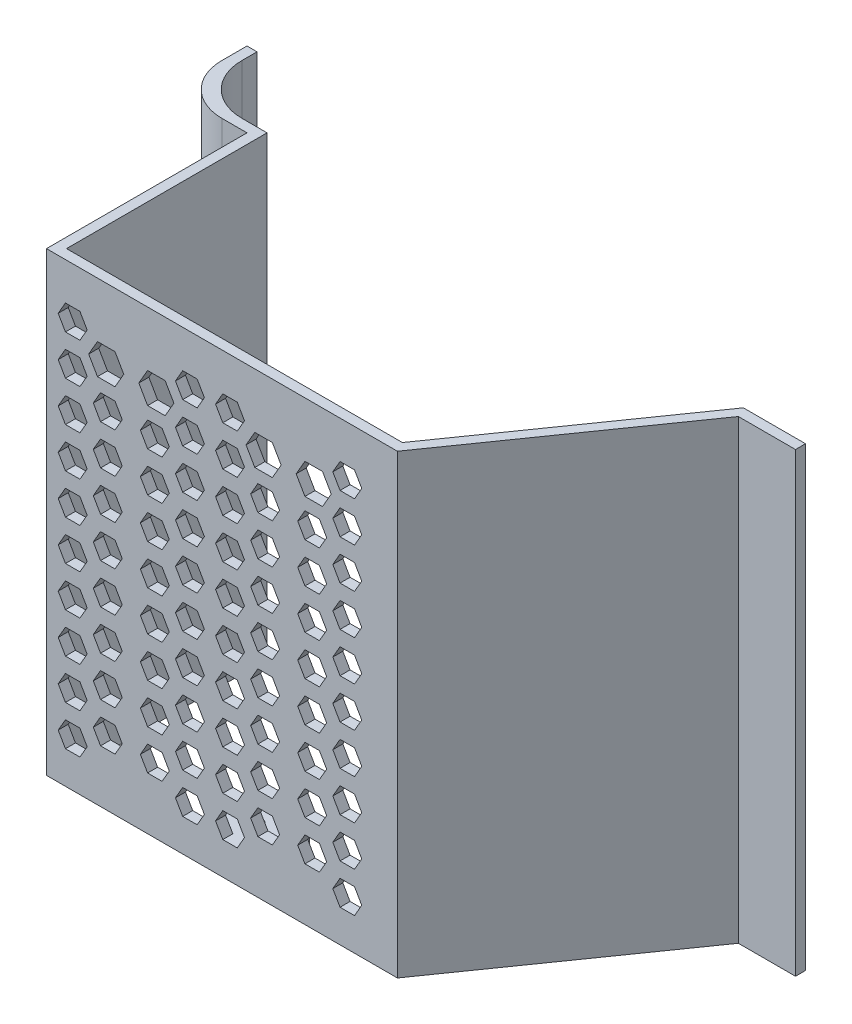
SolidWorks part; units mm, degrees
ref_plane "Ön Düzlem" through (0, 0, 0) normal (0, 0, 1) x (1, 0, 0)
ref_plane "Üst Düzlem" through (0, 0, 0) normal (0, 1, 0) x (1, 0, 0)
ref_plane "Sağ Düzlem" through (0, 0, 0) normal (1, 0, 0) x (0, 0, -1)
sketch "Çizim1" plane through (0, 0, 0) normal (0, 1, 0) x (1, 0, 0)
  line L0 (0, 0) -> (70, 0)
  line L5 (0, 0) -> (0, 30)
  line L8 (0, 30) -> (-3, 30)
  line L9 (-13, 40) -> (-13, 42)
  line L10 (-13, 42) -> (-11, 42)
  line L11 (70, 0) -> (99.4087, 42)
  line L12 (-1, 32) -> (2, 32)
  line L13 (2, 32) -> (2, 2)
  line L14 (2, 2) -> (69, 2)
  line L15 (69, 2) -> (97.0083, 42)
  line L16 (97.0083, 42) -> (99.4087, 42)
  arc A0 (-3, 30) -> (-13, 40) centre (-3, 40) cw
  arc A1 (-11, 42) -> (-1, 32) centre (-1, 42) ccw
  dimension "D3" = 10
  dimension "D1" = 70
  dimension "D2" = 30
extrude "Yükseklik-Ekstrüzyon1" add sketch "Çizim1" along normal blind 91
sketch "Çizim2" plane through (0, 0, 0) normal (0, 0, 1) x (1, 0, 0)
  line L0 (70, 91) -> (60, 91)
  line L1 (0, 91) -> (70, 91) construction
  line L2 (61.4434, 75.5) -> (62.8868, 73)
  line L3 (58.5566, 75.5) -> (61.4434, 75.5)
  line L4 (62.8868, 65) -> (61.4434, 67.5)
  line L5 (57.1132, 73) -> (58.5566, 75.5)
  line L6 (58.5566, 70.5) -> (57.1132, 73)
  line L7 (62.8868, 81) -> (61.4434, 83.5)
  line L8 (61.4434, 83.5) -> (58.5566, 83.5)
  line L9 (58.5566, 83.5) -> (57.1132, 81)
  line L10 (57.1132, 81) -> (58.5566, 78.5)
  line L11 (58.5566, 78.5) -> (61.4434, 78.5)
  line L12 (61.4434, 78.5) -> (62.8868, 81)
  line L13 (61.4434, 70.5) -> (58.5566, 70.5)
  line L14 (62.8868, 73) -> (61.4434, 70.5)
  line L15 (61.4434, 43.5) -> (62.8868, 41)
  line L16 (61.4434, 67.5) -> (58.5566, 67.5)
  line L17 (61.4434, 59.5) -> (62.8868, 57)
  line L18 (58.5566, 59.5) -> (61.4434, 59.5)
  line L19 (57.1132, 57) -> (58.5566, 59.5)
  line L20 (58.5566, 54.5) -> (57.1132, 57)
  line L21 (61.4434, 54.5) -> (58.5566, 54.5)
  line L22 (62.8868, 57) -> (61.4434, 54.5)
  line L23 (58.5566, 67.5) -> (57.1132, 65)
  line L24 (57.1132, 65) -> (58.5566, 62.5)
  line L25 (58.5566, 62.5) -> (61.4434, 62.5)
  line L26 (61.4434, 62.5) -> (62.8868, 65)
  line L27 (61.4434, 11.5) -> (62.8868, 9)
  line L28 (58.5566, 43.5) -> (61.4434, 43.5)
  line L29 (57.1132, 41) -> (58.5566, 43.5)
  line L30 (58.5566, 38.5) -> (57.1132, 41)
  line L31 (62.8868, 49) -> (61.4434, 51.5)
  line L32 (61.4434, 51.5) -> (58.5566, 51.5)
  line L33 (58.5566, 51.5) -> (57.1132, 49)
  line L34 (57.1132, 49) -> (58.5566, 46.5)
  line L35 (58.5566, 46.5) -> (61.4434, 46.5)
  line L36 (61.4434, 46.5) -> (62.8868, 49)
  line L37 (61.4434, 38.5) -> (58.5566, 38.5)
  line L38 (62.8868, 33) -> (61.4434, 35.5)
  line L39 (61.4434, 35.5) -> (58.5566, 35.5)
  line L40 (61.4434, 27.5) -> (62.8868, 25)
  line L41 (58.5566, 27.5) -> (61.4434, 27.5)
  line L42 (57.1132, 25) -> (58.5566, 27.5)
  line L43 (58.5566, 22.5) -> (57.1132, 25)
  line L44 (61.4434, 22.5) -> (58.5566, 22.5)
  line L45 (62.8868, 25) -> (61.4434, 22.5)
  line L46 (58.5566, 35.5) -> (57.1132, 33)
  line L47 (57.1132, 33) -> (58.5566, 30.5)
  line L48 (62.8868, 41) -> (61.4434, 38.5)
  line L49 (58.5566, 30.5) -> (61.4434, 30.5)
  line L50 (61.4434, 30.5) -> (62.8868, 33)
  line L51 (42.1699, 10.5) -> (40.7265, 13)
  line L52 (58.5566, 11.5) -> (61.4434, 11.5)
  line L53 (57.1132, 9) -> (58.5566, 11.5)
  line L54 (58.5566, 6.5) -> (57.1132, 9)
  line L55 (62.8868, 17) -> (61.4434, 19.5)
  line L56 (61.4434, 19.5) -> (58.5566, 19.5)
  line L57 (58.5566, 19.5) -> (57.1132, 17)
  line L58 (57.1132, 17) -> (58.5566, 14.5)
  line L59 (58.5566, 14.5) -> (61.4434, 14.5)
  line L60 (61.4434, 14.5) -> (62.8868, 17)
  line L61 (61.4434, 6.5) -> (58.5566, 6.5)
  line L62 (62.8868, 9) -> (61.4434, 6.5)
  line L63 (54.4434, 71.5) -> (55.8868, 69)
  line L64 (51.5566, 71.5) -> (54.4434, 71.5)
  line L65 (56.8066, 77) -> (55.0566, 80.0311)
  line L66 (55.0566, 80.0311) -> (51.5566, 80.0311)
  line L67 (51.5566, 80.0311) -> (49.8066, 77)
  line L68 (49.8066, 77) -> (51.5566, 73.9689)
  line L69 (51.5566, 73.9689) -> (55.0566, 73.9689)
  line L70 (55.0566, 73.9689) -> (56.8066, 77)
  line L71 (50.1132, 69) -> (51.5566, 71.5)
  line L72 (51.5566, 66.5) -> (50.1132, 69)
  line L73 (54.4434, 66.5) -> (51.5566, 66.5)
  line L74 (55.8868, 69) -> (54.4434, 66.5)
  line L75 (55.8868, 61) -> (54.4434, 63.5)
  line L76 (54.4434, 63.5) -> (51.5566, 63.5)
  line L77 (51.5566, 63.5) -> (50.1132, 61)
  line L78 (50.1132, 61) -> (51.5566, 58.5)
  line L79 (54.4434, 55.5) -> (55.8868, 53)
  line L80 (51.5566, 55.5) -> (54.4434, 55.5)
  line L81 (50.1132, 53) -> (51.5566, 55.5)
  line L82 (51.5566, 50.5) -> (50.1132, 53)
  line L83 (54.4434, 50.5) -> (51.5566, 50.5)
  line L84 (55.8868, 53) -> (54.4434, 50.5)
  line L85 (51.5566, 58.5) -> (54.4434, 58.5)
  line L86 (54.4434, 58.5) -> (55.8868, 61)
  line L87 (54.4434, 39.5) -> (55.8868, 37)
  line L88 (51.5566, 39.5) -> (54.4434, 39.5)
  line L89 (55.8868, 45) -> (54.4434, 47.5)
  line L90 (54.4434, 47.5) -> (51.5566, 47.5)
  line L91 (51.5566, 47.5) -> (50.1132, 45)
  line L92 (50.1132, 45) -> (51.5566, 42.5)
  line L93 (51.5566, 42.5) -> (54.4434, 42.5)
  line L94 (54.4434, 42.5) -> (55.8868, 45)
  line L95 (50.1132, 37) -> (51.5566, 39.5)
  line L96 (51.5566, 34.5) -> (50.1132, 37)
  line L97 (54.4434, 34.5) -> (51.5566, 34.5)
  line L98 (55.8868, 37) -> (54.4434, 34.5)
  line L99 (55.8868, 29) -> (54.4434, 31.5)
  line L100 (54.4434, 31.5) -> (51.5566, 31.5)
  line L101 (51.5566, 31.5) -> (50.1132, 29)
  line L102 (50.1132, 29) -> (51.5566, 26.5)
  line L103 (54.4434, 23.5) -> (55.8868, 21)
  line L104 (51.5566, 23.5) -> (54.4434, 23.5)
  line L105 (50.1132, 21) -> (51.5566, 23.5)
  line L106 (51.5566, 18.5) -> (50.1132, 21)
  line L107 (54.4434, 18.5) -> (51.5566, 18.5)
  line L108 (55.8868, 21) -> (54.4434, 18.5)
  line L109 (51.5566, 26.5) -> (54.4434, 26.5)
  line L110 (54.4434, 26.5) -> (55.8868, 29)
  line L111 (55.8868, 13) -> (54.4434, 15.5)
  line L112 (54.4434, 15.5) -> (51.5566, 15.5)
  line L113 (51.5566, 15.5) -> (50.1132, 13)
  line L114 (50.1132, 13) -> (51.5566, 10.5)
  line L115 (51.5566, 10.5) -> (54.4434, 10.5)
  line L116 (54.4434, 10.5) -> (55.8868, 13)
  line L117 (30.0566, 75.5) -> (31.5, 73)
  line L118 (45.0566, 10.5) -> (42.1699, 10.5)
  line L119 (46.5, 13) -> (45.0566, 10.5)
  line L120 (45.0566, 15.5) -> (46.5, 13)
  line L121 (42.1699, 15.5) -> (45.0566, 15.5)
  line L122 (40.7265, 13) -> (42.1699, 15.5)
  line L123 (42.1699, 26.5) -> (40.7265, 29)
  line L124 (45.0566, 26.5) -> (42.1699, 26.5)
  line L125 (40.7265, 21) -> (42.1699, 18.5)
  line L126 (42.1699, 18.5) -> (45.0566, 18.5)
  line L127 (45.0566, 18.5) -> (46.5, 21)
  line L128 (46.5, 21) -> (45.0566, 23.5)
  line L129 (45.0566, 23.5) -> (42.1699, 23.5)
  line L130 (42.1699, 23.5) -> (40.7265, 21)
  line L131 (46.5, 29) -> (45.0566, 26.5)
  line L132 (45.0566, 31.5) -> (46.5, 29)
  line L133 (42.1699, 31.5) -> (45.0566, 31.5)
  line L134 (40.7265, 29) -> (42.1699, 31.5)
  line L135 (40.7265, 37) -> (42.1699, 34.5)
  line L136 (42.1699, 34.5) -> (45.0566, 34.5)
  line L137 (45.0566, 34.5) -> (46.5, 37)
  line L138 (46.5, 37) -> (45.0566, 39.5)
  line L139 (42.1699, 42.5) -> (40.7265, 45)
  line L140 (45.0566, 42.5) -> (42.1699, 42.5)
  line L141 (46.5, 45) -> (45.0566, 42.5)
  line L142 (45.0566, 47.5) -> (46.5, 45)
  line L143 (42.1699, 47.5) -> (45.0566, 47.5)
  line L144 (40.7265, 45) -> (42.1699, 47.5)
  line L145 (45.0566, 39.5) -> (42.1699, 39.5)
  line L146 (42.1699, 39.5) -> (40.7265, 37)
  line L147 (42.1699, 58.5) -> (40.7265, 61)
  line L148 (45.0566, 58.5) -> (42.1699, 58.5)
  line L149 (40.7265, 53) -> (42.1699, 50.5)
  line L150 (42.1699, 50.5) -> (45.0566, 50.5)
  line L151 (45.0566, 50.5) -> (46.5, 53)
  line L152 (46.5, 53) -> (45.0566, 55.5)
  line L153 (45.0566, 55.5) -> (42.1699, 55.5)
  line L154 (42.1699, 55.5) -> (40.7265, 53)
  line L155 (46.5, 61) -> (45.0566, 58.5)
  line L156 (45.0566, 63.5) -> (46.5, 61)
  line L157 (42.1699, 63.5) -> (45.0566, 63.5)
  line L158 (40.7265, 61) -> (42.1699, 63.5)
  line L159 (40.7265, 69) -> (42.1699, 66.5)
  line L160 (42.1699, 66.5) -> (45.0566, 66.5)
  line L161 (45.0566, 66.5) -> (46.5, 69)
  line L162 (46.5, 69) -> (45.0566, 71.5)
  line L163 (41.5566, 73.9689) -> (39.8066, 77)
  line L164 (45.0566, 73.9689) -> (41.5566, 73.9689)
  line L165 (46.8066, 77) -> (45.0566, 73.9689)
  line L166 (45.0566, 80.0311) -> (46.8066, 77)
  line L167 (41.5566, 80.0311) -> (45.0566, 80.0311)
  line L168 (39.8066, 77) -> (41.5566, 80.0311)
  line L169 (45.0566, 71.5) -> (42.1699, 71.5)
  line L170 (42.1699, 71.5) -> (40.7265, 69)
  line L171 (33.7265, 9) -> (35.1699, 6.5)
  line L172 (35.1699, 6.5) -> (38.0566, 6.5)
  line L173 (35.1699, 14.5) -> (33.7265, 17)
  line L174 (38.0566, 14.5) -> (35.1699, 14.5)
  line L175 (39.5, 17) -> (38.0566, 14.5)
  line L176 (38.0566, 19.5) -> (39.5, 17)
  line L177 (35.1699, 19.5) -> (38.0566, 19.5)
  line L178 (33.7265, 17) -> (35.1699, 19.5)
  line L179 (38.0566, 6.5) -> (39.5, 9)
  line L180 (39.5, 9) -> (38.0566, 11.5)
  line L181 (38.0566, 11.5) -> (35.1699, 11.5)
  line L182 (35.1699, 30.5) -> (33.7265, 33)
  line L183 (38.0566, 30.5) -> (35.1699, 30.5)
  line L184 (33.7265, 41) -> (35.1699, 38.5)
  line L185 (39.5, 33) -> (38.0566, 30.5)
  line L186 (38.0566, 35.5) -> (39.5, 33)
  line L187 (33.7265, 25) -> (35.1699, 22.5)
  line L188 (35.1699, 22.5) -> (38.0566, 22.5)
  line L189 (38.0566, 22.5) -> (39.5, 25)
  line L190 (39.5, 25) -> (38.0566, 27.5)
  line L191 (38.0566, 27.5) -> (35.1699, 27.5)
  line L192 (35.1699, 27.5) -> (33.7265, 25)
  line L193 (35.1699, 35.5) -> (38.0566, 35.5)
  line L194 (33.7265, 33) -> (35.1699, 35.5)
  line L195 (35.1699, 38.5) -> (38.0566, 38.5)
  line L196 (35.1699, 46.5) -> (33.7265, 49)
  line L197 (38.0566, 46.5) -> (35.1699, 46.5)
  line L198 (39.5, 49) -> (38.0566, 46.5)
  line L199 (38.0566, 51.5) -> (39.5, 49)
  line L200 (35.1699, 51.5) -> (38.0566, 51.5)
  line L201 (33.7265, 49) -> (35.1699, 51.5)
  line L202 (38.0566, 38.5) -> (39.5, 41)
  line L203 (39.5, 41) -> (38.0566, 43.5)
  line L204 (38.0566, 43.5) -> (35.1699, 43.5)
  line L205 (35.1699, 11.5) -> (33.7265, 9)
  line L206 (35.1699, 62.5) -> (33.7265, 65)
  line L207 (38.0566, 62.5) -> (35.1699, 62.5)
  line L208 (39.5, 65) -> (38.0566, 62.5)
  line L209 (38.0566, 67.5) -> (39.5, 65)
  line L210 (33.7265, 57) -> (35.1699, 54.5)
  line L211 (35.1699, 54.5) -> (38.0566, 54.5)
  line L212 (38.0566, 54.5) -> (39.5, 57)
  line L213 (39.5, 57) -> (38.0566, 59.5)
  line L214 (38.0566, 59.5) -> (35.1699, 59.5)
  line L215 (35.1699, 59.5) -> (33.7265, 57)
  line L216 (35.1699, 67.5) -> (38.0566, 67.5)
  line L217 (35.1699, 43.5) -> (33.7265, 41)
  line L218 (33.7265, 73) -> (35.1699, 70.5)
  line L219 (35.1699, 70.5) -> (38.0566, 70.5)
  line L220 (35.1699, 78.5) -> (33.7265, 81)
  line L221 (38.0566, 78.5) -> (35.1699, 78.5)
  line L222 (39.5, 81) -> (38.0566, 78.5)
  line L223 (38.0566, 83.5) -> (39.5, 81)
  line L224 (35.1699, 83.5) -> (38.0566, 83.5)
  line L225 (33.7265, 81) -> (35.1699, 83.5)
  line L226 (38.0566, 70.5) -> (39.5, 73)
  line L227 (39.5, 73) -> (38.0566, 75.5)
  line L228 (33.7265, 65) -> (35.1699, 67.5)
  line L229 (38.0566, 75.5) -> (35.1699, 75.5)
  line L230 (35.1699, 75.5) -> (33.7265, 73)
  line L232 (27.1699, 75.5) -> (30.0566, 75.5)
  line L233 (31.5, 65) -> (30.0566, 67.5)
  line L234 (25.7265, 73) -> (27.1699, 75.5)
  line L235 (27.1699, 70.5) -> (25.7265, 73)
  line L236 (31.5, 81) -> (30.0566, 83.5)
  line L237 (30.0566, 83.5) -> (27.1699, 83.5)
  line L238 (27.1699, 83.5) -> (25.7265, 81)
  line L239 (25.7265, 81) -> (27.1699, 78.5)
  line L240 (27.1699, 78.5) -> (30.0566, 78.5)
  line L241 (30.0566, 78.5) -> (31.5, 81)
  line L242 (30.0566, 70.5) -> (27.1699, 70.5)
  line L243 (31.5, 73) -> (30.0566, 70.5)
  line L244 (30.0566, 43.5) -> (31.5, 41)
  line L245 (30.0566, 67.5) -> (27.1699, 67.5)
  line L246 (30.0566, 59.5) -> (31.5, 57)
  line L247 (27.1699, 59.5) -> (30.0566, 59.5)
  line L248 (25.7265, 57) -> (27.1699, 59.5)
  line L249 (27.1699, 54.5) -> (25.7265, 57)
  line L250 (30.0566, 54.5) -> (27.1699, 54.5)
  line L251 (31.5, 57) -> (30.0566, 54.5)
  line L252 (27.1699, 67.5) -> (25.7265, 65)
  line L253 (25.7265, 65) -> (27.1699, 62.5)
  line L254 (27.1699, 62.5) -> (30.0566, 62.5)
  line L255 (30.0566, 62.5) -> (31.5, 65)
  line L256 (30.0566, 11.5) -> (31.5, 9)
  line L257 (27.1699, 43.5) -> (30.0566, 43.5)
  line L258 (25.7265, 41) -> (27.1699, 43.5)
  line L259 (27.1699, 38.5) -> (25.7265, 41)
  line L260 (31.5, 49) -> (30.0566, 51.5)
  line L261 (30.0566, 51.5) -> (27.1699, 51.5)
  line L262 (27.1699, 51.5) -> (25.7265, 49)
  line L263 (25.7265, 49) -> (27.1699, 46.5)
  line L264 (27.1699, 46.5) -> (30.0566, 46.5)
  line L265 (30.0566, 46.5) -> (31.5, 49)
  line L266 (30.0566, 38.5) -> (27.1699, 38.5)
  line L267 (31.5, 33) -> (30.0566, 35.5)
  line L268 (30.0566, 35.5) -> (27.1699, 35.5)
  line L269 (30.0566, 27.5) -> (31.5, 25)
  line L270 (27.1699, 27.5) -> (30.0566, 27.5)
  line L271 (25.7265, 25) -> (27.1699, 27.5)
  line L272 (27.1699, 22.5) -> (25.7265, 25)
  line L273 (30.0566, 22.5) -> (27.1699, 22.5)
  line L274 (31.5, 25) -> (30.0566, 22.5)
  line L275 (27.1699, 35.5) -> (25.7265, 33)
  line L276 (25.7265, 33) -> (27.1699, 30.5)
  line L277 (31.5, 41) -> (30.0566, 38.5)
  line L278 (27.1699, 30.5) -> (30.0566, 30.5)
  line L279 (30.0566, 30.5) -> (31.5, 33)
  line L280 (27.1699, 11.5) -> (30.0566, 11.5)
  line L281 (25.7265, 9) -> (27.1699, 11.5)
  line L282 (27.1699, 6.5) -> (25.7265, 9)
  line L283 (31.5, 17) -> (30.0566, 19.5)
  line L284 (30.0566, 19.5) -> (27.1699, 19.5)
  line L285 (27.1699, 19.5) -> (25.7265, 17)
  line L286 (25.7265, 17) -> (27.1699, 14.5)
  line L287 (27.1699, 14.5) -> (30.0566, 14.5)
  line L288 (30.0566, 14.5) -> (31.5, 17)
  line L289 (30.0566, 6.5) -> (27.1699, 6.5)
  line L290 (31.5, 9) -> (30.0566, 6.5)
  line L291 (23.0566, 71.5) -> (24.5, 69)
  line L292 (20.1699, 71.5) -> (23.0566, 71.5)
  line L293 (25.4199, 77) -> (23.6699, 80.0311)
  line L294 (23.6699, 80.0311) -> (20.1699, 80.0311)
  line L295 (20.1699, 80.0311) -> (18.4199, 77)
  line L296 (18.4199, 77) -> (20.1699, 73.9689)
  line L297 (20.1699, 73.9689) -> (23.6699, 73.9689)
  line L298 (23.6699, 73.9689) -> (25.4199, 77)
  line L299 (18.7265, 69) -> (20.1699, 71.5)
  line L300 (20.1699, 66.5) -> (18.7265, 69)
  line L301 (23.0566, 66.5) -> (20.1699, 66.5)
  line L302 (24.5, 69) -> (23.0566, 66.5)
  line L303 (24.5, 61) -> (23.0566, 63.5)
  line L304 (23.0566, 63.5) -> (20.1699, 63.5)
  line L305 (20.1699, 63.5) -> (18.7265, 61)
  line L306 (18.7265, 61) -> (20.1699, 58.5)
  line L307 (23.0566, 55.5) -> (24.5, 53)
  line L308 (20.1699, 55.5) -> (23.0566, 55.5)
  line L309 (18.7265, 53) -> (20.1699, 55.5)
  line L310 (20.1699, 50.5) -> (18.7265, 53)
  line L311 (23.0566, 50.5) -> (20.1699, 50.5)
  line L312 (24.5, 53) -> (23.0566, 50.5)
  line L313 (20.1699, 58.5) -> (23.0566, 58.5)
  line L314 (23.0566, 58.5) -> (24.5, 61)
  line L315 (23.0566, 39.5) -> (24.5, 37)
  line L316 (20.1699, 39.5) -> (23.0566, 39.5)
  line L317 (24.5, 45) -> (23.0566, 47.5)
  line L318 (23.0566, 47.5) -> (20.1699, 47.5)
  line L319 (20.1699, 47.5) -> (18.7265, 45)
  line L320 (18.7265, 45) -> (20.1699, 42.5)
  line L321 (20.1699, 42.5) -> (23.0566, 42.5)
  line L322 (23.0566, 42.5) -> (24.5, 45)
  line L323 (18.7265, 37) -> (20.1699, 39.5)
  line L324 (20.1699, 34.5) -> (18.7265, 37)
  line L325 (23.0566, 34.5) -> (20.1699, 34.5)
  line L326 (24.5, 37) -> (23.0566, 34.5)
  line L327 (24.5, 29) -> (23.0566, 31.5)
  line L328 (23.0566, 31.5) -> (20.1699, 31.5)
  line L329 (20.1699, 31.5) -> (18.7265, 29)
  line L330 (18.7265, 29) -> (20.1699, 26.5)
  line L331 (23.0566, 23.5) -> (24.5, 21)
  line L332 (20.1699, 23.5) -> (23.0566, 23.5)
  line L333 (18.7265, 21) -> (20.1699, 23.5)
  line L334 (20.1699, 18.5) -> (18.7265, 21)
  line L335 (23.0566, 18.5) -> (20.1699, 18.5)
  line L336 (24.5, 21) -> (23.0566, 18.5)
  line L337 (20.1699, 26.5) -> (23.0566, 26.5)
  line L338 (23.0566, 26.5) -> (24.5, 29)
  line L339 (24.5, 13) -> (23.0566, 15.5)
  line L340 (23.0566, 15.5) -> (20.1699, 15.5)
  line L341 (20.1699, 15.5) -> (18.7265, 13)
  line L342 (18.7265, 13) -> (20.1699, 10.5)
  line L343 (20.1699, 10.5) -> (23.0566, 10.5)
  line L344 (10.7831, 10.5) -> (9.3397, 13)
  line L345 (13.6699, 10.5) -> (10.7831, 10.5)
  line L346 (15.1132, 13) -> (13.6699, 10.5)
  line L347 (13.6699, 15.5) -> (15.1132, 13)
  line L348 (10.7831, 15.5) -> (13.6699, 15.5)
  line L349 (9.3397, 13) -> (10.7831, 15.5)
  line L350 (10.7831, 26.5) -> (9.3397, 29)
  line L351 (13.6699, 26.5) -> (10.7831, 26.5)
  line L352 (9.3397, 21) -> (10.7831, 18.5)
  line L353 (10.7831, 18.5) -> (13.6699, 18.5)
  line L354 (13.6699, 18.5) -> (15.1132, 21)
  line L355 (15.1132, 21) -> (13.6699, 23.5)
  line L356 (13.6699, 23.5) -> (10.7831, 23.5)
  line L357 (10.7831, 23.5) -> (9.3397, 21)
  line L358 (15.1132, 29) -> (13.6699, 26.5)
  line L359 (13.6699, 31.5) -> (15.1132, 29)
  line L360 (10.7831, 31.5) -> (13.6699, 31.5)
  line L361 (9.3397, 29) -> (10.7831, 31.5)
  line L362 (9.3397, 37) -> (10.7831, 34.5)
  line L363 (10.7831, 34.5) -> (13.6699, 34.5)
  line L364 (13.6699, 34.5) -> (15.1132, 37)
  line L365 (15.1132, 37) -> (13.6699, 39.5)
  line L366 (10.7831, 42.5) -> (9.3397, 45)
  line L367 (13.6699, 42.5) -> (10.7831, 42.5)
  line L368 (15.1132, 45) -> (13.6699, 42.5)
  line L369 (13.6699, 47.5) -> (15.1132, 45)
  line L370 (10.7831, 47.5) -> (13.6699, 47.5)
  line L371 (9.3397, 45) -> (10.7831, 47.5)
  line L372 (13.6699, 39.5) -> (10.7831, 39.5)
  line L373 (10.7831, 39.5) -> (9.3397, 37)
  line L374 (10.7831, 58.5) -> (9.3397, 61)
  line L375 (13.6699, 58.5) -> (10.7831, 58.5)
  line L376 (9.3397, 53) -> (10.7831, 50.5)
  line L377 (10.7831, 50.5) -> (13.6699, 50.5)
  line L378 (13.6699, 50.5) -> (15.1132, 53)
  line L379 (15.1132, 53) -> (13.6699, 55.5)
  line L380 (13.6699, 55.5) -> (10.7831, 55.5)
  line L381 (10.7831, 55.5) -> (9.3397, 53)
  line L382 (15.1132, 61) -> (13.6699, 58.5)
  line L383 (13.6699, 63.5) -> (15.1132, 61)
  line L384 (10.7831, 63.5) -> (13.6699, 63.5)
  line L385 (9.3397, 61) -> (10.7831, 63.5)
  line L386 (9.3397, 69) -> (10.7831, 66.5)
  line L387 (10.7831, 66.5) -> (13.6699, 66.5)
  line L388 (13.6699, 66.5) -> (15.1132, 69)
  line L389 (15.1132, 69) -> (13.6699, 71.5)
  line L390 (10.1699, 73.9689) -> (8.4199, 77)
  line L391 (13.6699, 73.9689) -> (10.1699, 73.9689)
  line L392 (15.4199, 77) -> (13.6699, 73.9689)
  line L393 (13.6699, 80.0311) -> (15.4199, 77)
  line L394 (10.1699, 80.0311) -> (13.6699, 80.0311)
  line L395 (8.4199, 77) -> (10.1699, 80.0311)
  line L396 (13.6699, 71.5) -> (10.7831, 71.5)
  line L397 (10.7831, 71.5) -> (9.3397, 69)
  line L398 (2.3397, 9) -> (3.7831, 6.5)
  line L399 (3.7831, 6.5) -> (6.6699, 6.5)
  line L400 (3.7831, 14.5) -> (2.3397, 17)
  line L401 (6.6699, 14.5) -> (3.7831, 14.5)
  line L402 (8.1132, 17) -> (6.6699, 14.5)
  line L403 (6.6699, 19.5) -> (8.1132, 17)
  line L404 (3.7831, 19.5) -> (6.6699, 19.5)
  line L405 (2.3397, 17) -> (3.7831, 19.5)
  line L406 (6.6699, 6.5) -> (8.1132, 9)
  line L407 (8.1132, 9) -> (6.6699, 11.5)
  line L408 (6.6699, 11.5) -> (3.7831, 11.5)
  line L409 (23.0566, 10.5) -> (24.5, 13)
  line L410 (3.7831, 30.5) -> (2.3397, 33)
  line L411 (6.6699, 30.5) -> (3.7831, 30.5)
  line L412 (2.3397, 41) -> (3.7831, 38.5)
  line L413 (8.1132, 33) -> (6.6699, 30.5)
  line L414 (6.6699, 35.5) -> (8.1132, 33)
  line L415 (2.3397, 25) -> (3.7831, 22.5)
  line L416 (3.7831, 22.5) -> (6.6699, 22.5)
  line L417 (6.6699, 22.5) -> (8.1132, 25)
  line L418 (8.1132, 25) -> (6.6699, 27.5)
  line L419 (6.6699, 27.5) -> (3.7831, 27.5)
  line L420 (3.7831, 27.5) -> (2.3397, 25)
  line L421 (3.7831, 35.5) -> (6.6699, 35.5)
  line L422 (2.3397, 33) -> (3.7831, 35.5)
  line L423 (3.7831, 38.5) -> (6.6699, 38.5)
  line L424 (3.7831, 46.5) -> (2.3397, 49)
  line L425 (6.6699, 46.5) -> (3.7831, 46.5)
  line L426 (8.1132, 49) -> (6.6699, 46.5)
  line L427 (6.6699, 51.5) -> (8.1132, 49)
  line L428 (3.7831, 51.5) -> (6.6699, 51.5)
  line L429 (2.3397, 49) -> (3.7831, 51.5)
  line L430 (6.6699, 38.5) -> (8.1132, 41)
  line L431 (8.1132, 41) -> (6.6699, 43.5)
  line L432 (6.6699, 43.5) -> (3.7831, 43.5)
  line L433 (3.7831, 11.5) -> (2.3397, 9)
  line L434 (3.7831, 62.5) -> (2.3397, 65)
  line L435 (6.6699, 62.5) -> (3.7831, 62.5)
  line L436 (8.1132, 65) -> (6.6699, 62.5)
  line L437 (6.6699, 67.5) -> (8.1132, 65)
  line L438 (2.3397, 57) -> (3.7831, 54.5)
  line L439 (3.7831, 54.5) -> (6.6699, 54.5)
  line L440 (6.6699, 54.5) -> (8.1132, 57)
  line L441 (8.1132, 57) -> (6.6699, 59.5)
  line L442 (6.6699, 59.5) -> (3.7831, 59.5)
  line L443 (3.7831, 59.5) -> (2.3397, 57)
  line L444 (3.7831, 67.5) -> (6.6699, 67.5)
  line L445 (3.7831, 43.5) -> (2.3397, 41)
  line L446 (2.3397, 73) -> (3.7831, 70.5)
  line L447 (3.7831, 70.5) -> (6.6699, 70.5)
  line L448 (3.7831, 78.5) -> (2.3397, 81)
  line L449 (6.6699, 78.5) -> (3.7831, 78.5)
  line L450 (8.1132, 81) -> (6.6699, 78.5)
  line L451 (6.6699, 83.5) -> (8.1132, 81)
  line L452 (3.7831, 83.5) -> (6.6699, 83.5)
  line L453 (2.3397, 81) -> (3.7831, 83.5)
  line L454 (6.6699, 70.5) -> (8.1132, 73)
  line L455 (8.1132, 73) -> (6.6699, 75.5)
  line L456 (2.3397, 65) -> (3.7831, 67.5)
  line L457 (6.6699, 75.5) -> (3.7831, 75.5)
  line L458 (3.7831, 75.5) -> (2.3397, 73)
  circle A0 centre (60, 81) radius 2.5 construction
  circle A1 centre (60, 73) radius 2.5 construction
  circle A2 centre (60, 65) radius 2.5 construction
  circle A3 centre (60, 57) radius 2.5 construction
  circle A4 centre (60, 49) radius 2.5 construction
  circle A5 centre (60, 41) radius 2.5 construction
  circle A6 centre (60, 33) radius 2.5 construction
  circle A7 centre (60, 25) radius 2.5 construction
  circle A8 centre (60, 17) radius 2.5 construction
  circle A9 centre (60, 9) radius 2.5 construction
  circle A10 centre (53.3066, 77) radius 3.0311 construction
  circle A11 centre (53, 69) radius 2.5 construction
  circle A12 centre (53, 61) radius 2.5 construction
  circle A13 centre (53, 53) radius 2.5 construction
  circle A14 centre (53, 45) radius 2.5 construction
  circle A15 centre (53, 37) radius 2.5 construction
  circle A16 centre (53, 29) radius 2.5 construction
  circle A17 centre (53, 21) radius 2.5 construction
  circle A18 centre (53, 13) radius 2.5 construction
  circle A19 centre (43.6132, 13) radius 2.5 construction
  circle A20 centre (43.6132, 21) radius 2.5 construction
  circle A21 centre (43.6132, 29) radius 2.5 construction
  circle A22 centre (43.6132, 37) radius 2.5 construction
  circle A23 centre (43.6132, 45) radius 2.5 construction
  circle A24 centre (43.6132, 53) radius 2.5 construction
  circle A25 centre (43.6132, 61) radius 2.5 construction
  circle A26 centre (43.6132, 69) radius 2.5 construction
  circle A27 centre (43.3066, 77) radius 3.0311 construction
  circle A28 centre (36.6132, 9) radius 2.5 construction
  circle A29 centre (36.6132, 17) radius 2.5 construction
  circle A30 centre (36.6132, 25) radius 2.5 construction
  circle A31 centre (36.6132, 33) radius 2.5 construction
  circle A32 centre (36.6132, 41) radius 2.5 construction
  circle A33 centre (36.6132, 49) radius 2.5 construction
  circle A34 centre (36.6132, 57) radius 2.5 construction
  circle A35 centre (36.6132, 65) radius 2.5 construction
  circle A36 centre (36.6132, 73) radius 2.5 construction
  circle A37 centre (36.6132, 81) radius 2.5 construction
  circle A38 centre (28.6132, 81) radius 2.5 construction
  circle A39 centre (28.6132, 73) radius 2.5 construction
  circle A40 centre (28.6132, 65) radius 2.5 construction
  circle A41 centre (28.6132, 57) radius 2.5 construction
  circle A42 centre (28.6132, 49) radius 2.5 construction
  circle A43 centre (28.6132, 41) radius 2.5 construction
  circle A44 centre (28.6132, 33) radius 2.5 construction
  circle A45 centre (28.6132, 25) radius 2.5 construction
  circle A46 centre (28.6132, 17) radius 2.5 construction
  circle A47 centre (28.6132, 9) radius 2.5 construction
  circle A48 centre (21.9199, 77) radius 3.0311 construction
  circle A49 centre (21.6132, 69) radius 2.5 construction
  circle A50 centre (21.6132, 61) radius 2.5 construction
  circle A51 centre (21.6132, 53) radius 2.5 construction
  circle A52 centre (21.6132, 45) radius 2.5 construction
  circle A53 centre (21.6132, 37) radius 2.5 construction
  circle A54 centre (21.6132, 29) radius 2.5 construction
  circle A55 centre (21.6132, 21) radius 2.5 construction
  circle A56 centre (21.6132, 13) radius 2.5 construction
  circle A57 centre (12.2265, 13) radius 2.5 construction
  circle A58 centre (12.2265, 21) radius 2.5 construction
  circle A59 centre (12.2265, 29) radius 2.5 construction
  circle A60 centre (12.2265, 37) radius 2.5 construction
  circle A61 centre (12.2265, 45) radius 2.5 construction
  circle A62 centre (12.2265, 53) radius 2.5 construction
  circle A63 centre (12.2265, 61) radius 2.5 construction
  circle A64 centre (12.2265, 69) radius 2.5 construction
  circle A65 centre (11.9199, 77) radius 3.0311 construction
  circle A66 centre (5.2265, 9) radius 2.5 construction
  circle A67 centre (5.2265, 17) radius 2.5 construction
  circle A68 centre (5.2265, 25) radius 2.5 construction
  circle A69 centre (5.2265, 33) radius 2.5 construction
  circle A70 centre (5.2265, 41) radius 2.5 construction
  circle A71 centre (5.2265, 49) radius 2.5 construction
  circle A72 centre (5.2265, 57) radius 2.5 construction
  circle A73 centre (5.2265, 65) radius 2.5 construction
  circle A74 centre (5.2265, 73) radius 2.5 construction
  circle A75 centre (5.2265, 81) radius 2.5 construction
extrude "Kes-Ekstrüzyon1" cut sketch "Çizim2" against normal blind 5 contours L408 L433 L398 L399 L406 L407 | L349 L348 L347 L346 L345 L344 | L402 L401 L400 L405 L404 L403 | L417 L418 L419 L420 L415 L416 | L357 L352 L353 L354 L355 L356 | L334 L333 L332 L331 L336 L335 | L340 L341 L342 L343 L409 L339 | L286 L287 L288 L283 L284 L285 | L173 L178 L177 L176 L175 L174 | L280 L256 L290 L289 L282 L281 | L171 L172 L179 L180 L181 L205 | L51 L122 L121 L120 L119 L118 | L126 L127 L128 L129 L130 L125 | L106 L105 L104 L103 L108 L107 | L113 L114 L115 L116 L111 L112 | L58 L59 L60 L55 L56 L57 | L53 L52 L27 L62 L61 L54 | L44 L43 L42 L41 L40 L45 | L110 L99 L100 L101 L102 L109 | L131 L124 L123 L134 L133 L132 | L189 L190 L191 L192 L187 L188 | L274 L273 L272 L271 L270 L269 | L338 L327 L328 L329 L330 L337 | L358 L351 L350 L361 L360 L359 | L413 L411 L410 L422 L421 L414 | L363 L364 L365 L372 L373 L362 | L325 L324 L323 L316 L315 L326 | L278 L279 L267 L268 L275 L276 | L183 L182 L194 L193 L186 L185 | L136 L137 L138 L145 L146 L135 | L97 L96 L95 L88 L87 L98 | L49 L50 L38 L39 L46 L47 | L430 L431 L432 L445 L412 L423 | L367 L366 L371 L370 L369 L368 | L426 L425 L424 L429 L428 L427 | L377 L378 L379 L380 L381 L376 | L440 L441 L442 L443 L438 L439 | L375 L374 L385 L384 L383 L382 | L436 L435 L434 L456 L444 L437 | L387 L388 L389 L396 L397 L386 | L454 L455 L457 L458 L446 L447 | L391 L390 L395 L394 L393 L392 | L450 L449 L448 L453 L452 L451 | L297 L298 L293 L294 L295 L296 | L301 L300 L299 L292 L291 L302 | L313 L314 L303 L304 L305 L306 | L308 L307 L312 L311 L310 L309 | L318 L319 L320 L321 L322 L317 | L257 L244 L277 L266 L259 L258 | L204 L217 L184 L195 L202 L203 | L37 L30 L29 L28 L15 L48 | L35 L36 L31 L32 L33 L34 | L93 L94 L89 L90 L91 L92 | L140 L139 L144 L143 L142 L141 | L197 L196 L201 L200 L199 L198 | L264 L265 L260 L261 L262 L263 | L250 L249 L248 L247 L246 L251 | L83 L82 L81 L80 L79 L84 | L150 L151 L152 L153 L154 L149 | L211 L212 L213 L214 L215 L210 | L148 L147 L158 L157 L156 L155 | L85 L86 L75 L76 L77 L78 | L21 L20 L19 L18 L17 L22 | L25 L26 L4 L16 L23 L24 | L73 L72 L71 L64 L63 L74 | L160 L161 L162 L169 L170 L159 | L207 L206 L228 L216 L209 L208 | L254 L255 L233 L245 L252 L253 | L242 L235 L234 L232 L117 L243 | L240 L241 L236 L237 L238 L239 | L221 L220 L225 L224 L223 L222 | L219 L226 L227 L229 L230 L218 | L164 L163 L168 L167 L166 L165 | L69 L70 L65 L66 L67 L68 | L13 L6 L5 L3 L2 L14 | L11 L12 L7 L8 L9 L10
sketch "Çizim3" plane through (0, 0, 0) normal (0, 1, 0) x (1, 0, 0)
  line L0 (99.4087, 42) -> (109.4087, 42)
  line L1 (109.4087, 42) -> (109.4087, 40)
  line L2 (109.4087, 40) -> (98.0083, 40)
  line L3 (70, 0) -> (99.4087, 42) construction
  line L4 (98.0083, 40) -> (99.4087, 42)
extrude "Yükseklik-Ekstrüzyon2" add sketch "Çizim3" along normal blind 91
sketch "Çizim8" plane through (0, 91, 0) normal (0, 1, 0) x (1, 0, 0)
  line L0 (0, 30) -> (5.7676, 30)
  line L1 (5.7676, 30) -> (5.7676, 46.9805)
  line L2 (5.7676, 46.9805) -> (-19.6704, 46.9805)
  line L3 (-19.6704, 46.9805) -> (-19.6704, 30)
  line L4 (-19.6704, 30) -> (0, 30)
extrude "Kes-Ekstrüzyon4" cut sketch "Çizim8" against normal blind 95
sketch "Çizim9" plane through (0, 91, 0) normal (0, 1, 0) x (1, 0, 0)
  line L0 (0, 30) -> (0, 40)
  line L3 (2, 30) -> (0, 30)
  line L4 (0, 40) -> (-5, 40)
  line L5 (-15, 50) -> (-15, 55)
  line L6 (-15, 55) -> (-13, 55)
  line L7 (-13, 55) -> (-13, 52)
  line L8 (-3, 42) -> (2, 42)
  line L9 (2, 42) -> (2, 30)
  arc A0 (-5, 40) -> (-15, 50) centre (-5, 50) cw
  arc A1 (-13, 52) -> (-3, 42) centre (-3, 52) ccw
  dimension "D1" = 10
extrude "Yükseklik-Ekstrüzyon5" add sketch "Çizim9" against normal blind 91
sketch "Çizim12" plane through (0, 0, -2) normal (0, 0, -1) x (-1, 0, 0)
  line L0 (-69, 0) -> (-2, 0) construction
  line L2 (-30.5, 0) -> (-30.5, 6.5)
  line L3 (-30.5, 6.5) -> (-40.5, 6.5)
  line L4 (-40.5, 0) -> (-40.5, 6.5)
  line L7 (-30.5, 0) -> (-40.5, 0)
  point P0 (-35.5, 0)
  dimension "D1" = 10
extrude "Yükseklik-Ekstrüzyon7" add sketch "Çizim12" along normal blind 10
sketch "Çizim13" plane through (0, 0, 0) normal (0, -1, 0) x (1, 0, 0)
  circle A0 centre (35.5, -6) radius 1.5
extrude "Kes-Ekstrüzyon6" cut sketch "Çizim13" against normal blind 10
